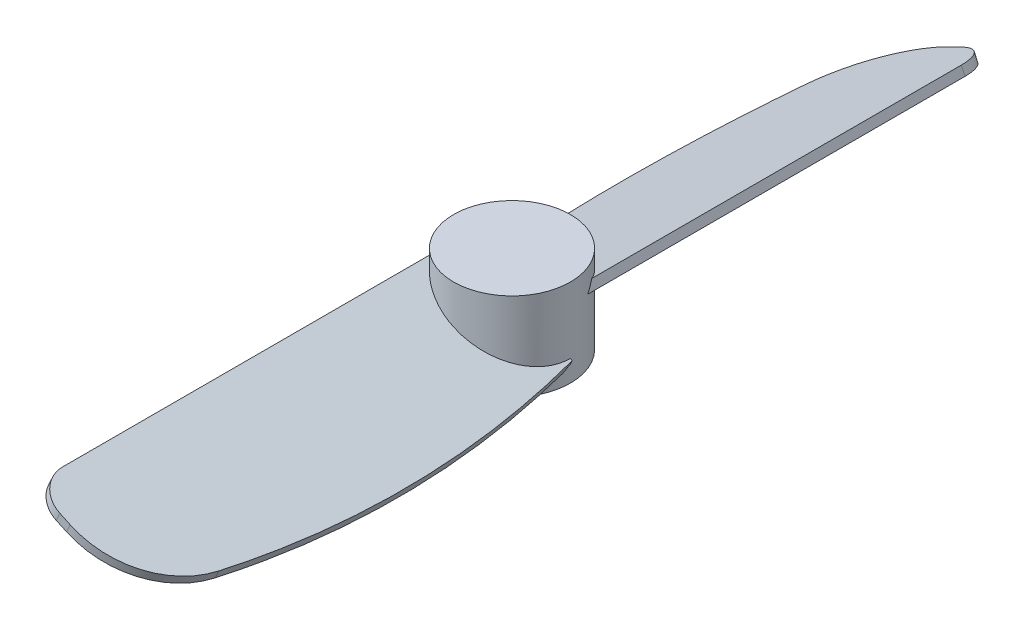
SolidWorks part; units mm, degrees
ref_plane "Front Plane" through (0, 0, 0) normal (0, 0, 1) x (1, 0, 0)
ref_plane "Top Plane" through (0, 0, 0) normal (0, 1, 0) x (1, 0, 0)
ref_plane "Right Plane" through (0, 0, 0) normal (1, 0, 0) x (0, 0, -1)
sketch "Sketch1" plane through (0, 0, 0) normal (0, 1, 0) x (1, 0, 0)
  circle A0 centre (0, 0) radius 2
  dimension "D1" = 4
extrude "Boss-Extrude1" add sketch "Sketch1" along normal blind 3
sketch "Sketch2" plane through (0, 0, 0) normal (0, 0, 1) x (1, 0, 0)
  line L0 (0, 3) -> (0, 0) construction
  line L1 (2, 3) -> (-2, 3) construction
  line L2 (-2, 1.5) -> (23, 1.5) construction
  line L3 (-2, 3) -> (-2, 0) construction
  line L4 (-2, 2.4326) -> (2, 0.5674)
  point P11 (0, 1.5)
  point P12 (0, 1.5)
  dimension "D1" = 25
ref_plane "Plane1" through (0.5745, 1.2321, 0) normal (-0.4226, -0.9063, 0) x (0.9063, -0.4226, 0)
sketch "Sketch3" plane through (0.5745, 1.2321, 0) normal (-0.4226, -0.9063, 0) x (0.9063, -0.4226, 0)
  line L0 (-2.4465, 0) -> (20.2112, 0) construction
  line L1 (-1.826, 0) -> (-2.6181, 0.6103)
  line L2 (-2.8407, 0) -> (1.5728, 0) construction
  line L3 (-2.6181, 0.6103) -> (-2.6181, 13.6447)
  line L4 (-1.6181, 14.6447) -> (-1.2299, 14.6447)
  line L5 (-1.826, 0) -> (1.5728, 0)
  arc A0 (1.7139, 12.2228) -> (-1.2299, 14.6447) centre (-1.2299, 11.6447) ccw
  arc A1 (-2.6181, 13.6447) -> (-1.6181, 14.6447) centre (-1.6181, 13.6447) cw
  spline S0 degree 3 poles (1.5728, 0) (2.4627, 4.0593) (2.5064, 8.1871) (1.7139, 12.2228) knots 0 0 0 0 0.833038 0.833038 0.833038 0.833038
  point P9 (-1.424, 14.6447)
  dimension "D3" = 3
  dimension "D4" = 1
  dimension "D1" = 14.6447
  dimension "D2" = 1
extrude "Boss-Extrude2" add sketch "Sketch3" along normal mid plane 0.3
ref_axis "Axis1" through (0, 3.15, 0) along (0, -1, 0)
pattern_circular "CirPattern1" count 2 over 360 about axis through (0, 3.15, 0) along (0, -1, 0) of "Boss-Extrude2"
